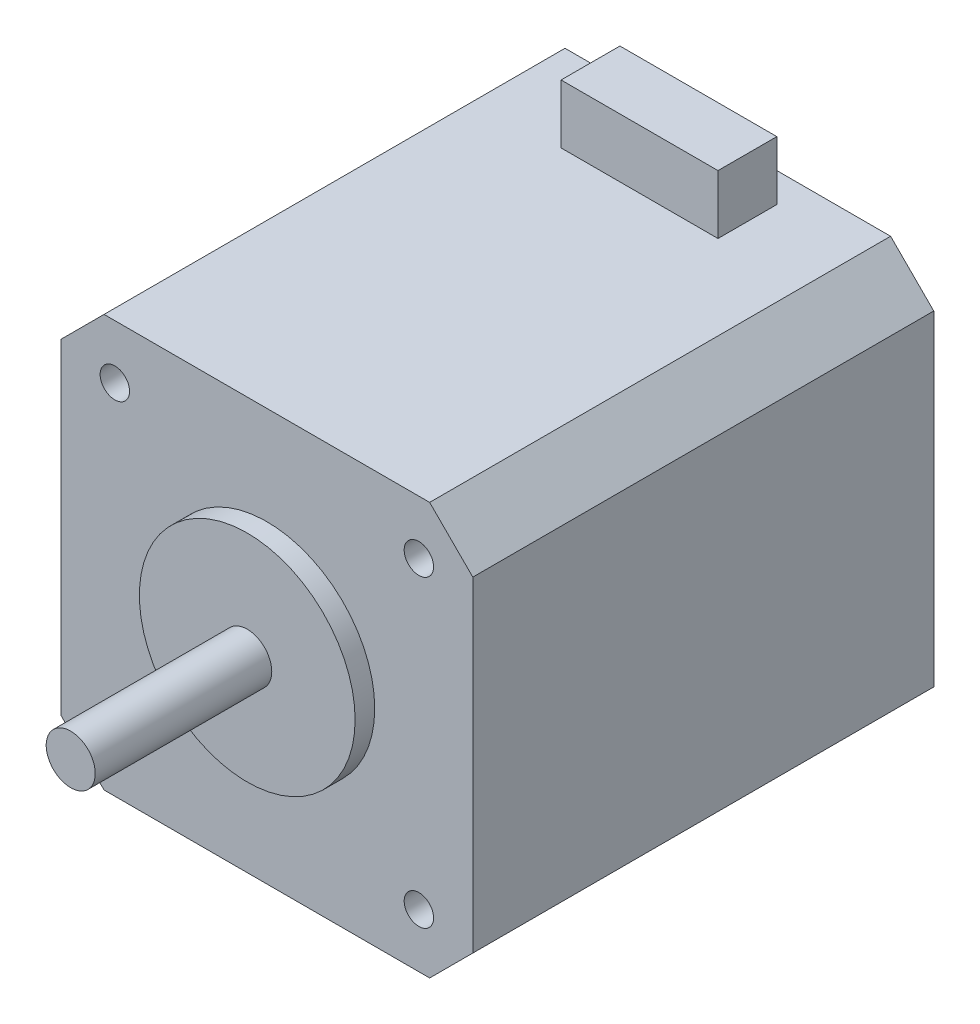
SolidWorks part; units mm, degrees
ref_plane "前视基准面" through (0, 0, 0) normal (0, 0, 1) x (1, 0, 0)
ref_plane "上视基准面" through (0, 0, 0) normal (0, 1, 0) x (1, 0, 0)
ref_plane "右视基准面" through (0, 0, 0) normal (1, 0, 0) x (0, 0, -1)
sketch "草图1" plane through (0, 0, 0) normal (0, 0, 1) x (1, 0, 0)
  line L0 (0, 0) -> (31.3879, 0) construction
  line L1 (0, 0) -> (0, 21.2989) construction
  line L2 (21, 0) -> (21, 16.6)
  line L3 (16.6, 21) -> (0, 21)
  line L4 (21, 16.6) -> (16.6, 21)
  line L5 (0, -21) -> (16.6, -21)
  line L6 (16.6, -21) -> (21, -16.6)
  line L7 (21, -16.6) -> (21, 0)
  line L8 (-21, 0) -> (-21, -16.6)
  line L9 (-21, -16.6) -> (-16.6, -21)
  line L10 (-16.6, -21) -> (0, -21)
  line L11 (0, 21) -> (-16.6, 21)
  line L12 (-16.6, 21) -> (-21, 16.6)
  line L13 (-21, 16.6) -> (-21, 0)
  circle A0 centre (15.5, 15.5) radius 1.5
  circle A1 centre (15.5, -15.5) radius 1.5
  circle A2 centre (-15.5, -15.5) radius 1.5
  circle A3 centre (-15.5, 15.5) radius 1.5
  point P5 (21, 21)
  point P32 (0, 0)
  dimension "D5" = 3
  dimension "D1" = 42
  dimension "D2" = 42
  dimension "D3" = 31
  dimension "D4" = 31
  dimension "D6" = 4
extrude "凸台-拉伸1" add sketch "草图1" along normal blind 47
sketch "草图2" plane through (0, 0, 47) normal (0, 0, 1) x (1, 0, 0)
  circle A0 centre (0, 0) radius 11
  dimension "D1" = 22
extrude "凸台-拉伸2" add sketch "草图2" along normal blind 2 contours A0
sketch "草图3" plane through (0, 0, 47) normal (0, 0, 1) x (1, 0, 0)
  circle A0 centre (0, 0) radius 2.5
  dimension "D1" = 5
extrude "凸台-拉伸3" add sketch "草图3" along normal blind 20
sketch "草图4" plane through (0, 21, 0) normal (0, 1, 0) x (1, 0, 0)
  line L0 (-8, -9) -> (8, -9)
  line L1 (16.6, 0) -> (-16.6, 0) construction
  line L2 (0, 0) -> (0, 3.5781) construction
  line L3 (-8, -9) -> (-8, -3)
  line L4 (-8, -3) -> (8, -3)
  line L5 (8, -3) -> (8, -9)
  dimension "D1" = 9
  dimension "D2" = 8
  dimension "D3" = 8
  dimension "D4" = 3
extrude "凸台-拉伸4" add sketch "草图4" along normal blind 6 contours L5 L0 L3 L4
